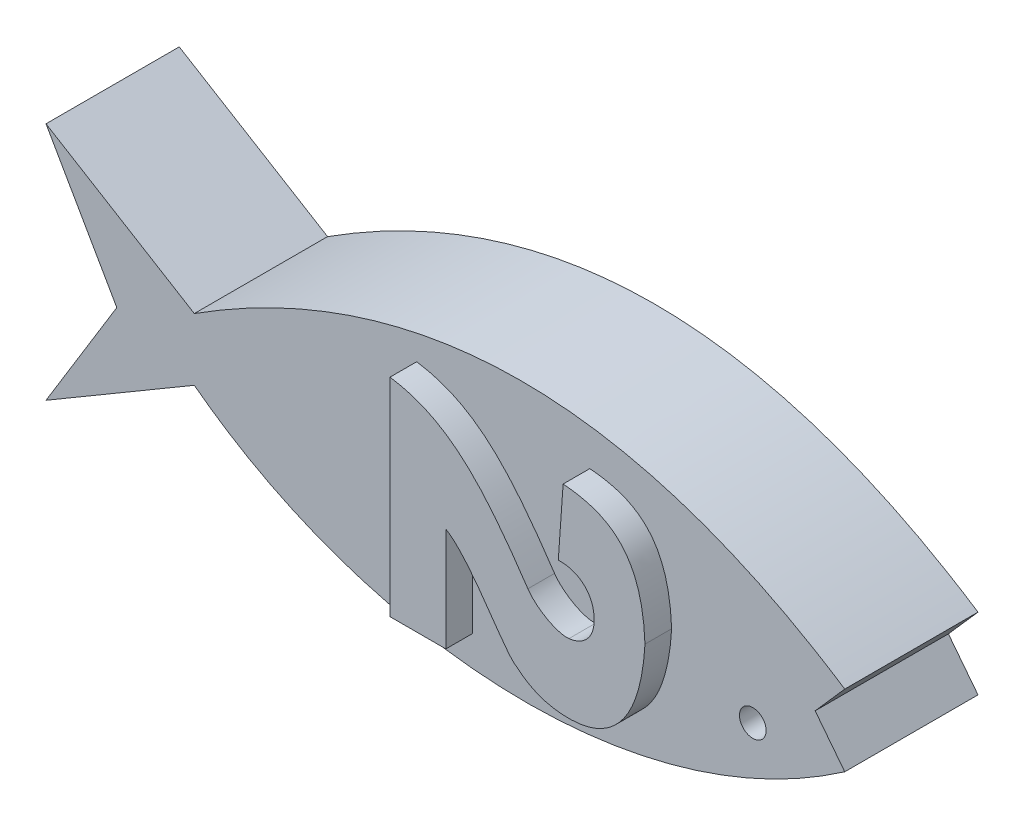
SolidWorks part; units mm, degrees
ref_plane "Front" through (0, 0, 0) normal (0, 0, 1) x (1, 0, 0)
ref_plane "Top" through (0, 0, 0) normal (0, 1, 0) x (1, 0, 0)
ref_plane "Right" through (0, 0, 0) normal (1, 0, 0) x (0, 0, -1)
sketch "Sketch2" plane through (0, 0, 0) normal (0, 0, -1) x (1, 0, 0)
  line L0 (29.973, 6.6427) -> (28.8624, 5.2157)
  line L1 (28.8624, 5.2157) -> (29.973, 3.9538)
  line L2 (5.5653, 6.2857) -> (0, 9.5561)
  line L3 (0, 9.5561) -> (2.6565, 5.2157)
  line L4 (2.6565, 5.2157) -> (0, 0.5701)
  line L5 (0, 0.5701) -> (5.5653, 3.9538)
  circle A0 centre (26.5226, 6.7807) radius 0.5001
  spline S0 degree 3 poles (5.5653, 6.2857) (12.0373, 11.2173) (22.1418, 12.0787) (29.973, 6.6427) knots 0 0 0 0 1 1 1 1
  spline S1 degree 2 poles (5.5653, 3.9538) (17.9191, -3.9397) (29.973, 3.9538) knots 0 0 0 1 1 1
extrude "Boss-Extrude1" add sketch "Sketch2" against normal blind 5
ref_plane "Fish Top Plane" through (0, 0, 5) normal (0, 0, 1) x (-1, 0, 0)
sketch "Sketch4" plane through (0, 0, 5) normal (0, 0, 1) x (-1, 0, 0)
  line L0 (-13.9083, 1.3496) -> (-13.9083, 9.134)
  line L1 (-13.9083, 9.134) -> (-16.0046, 9.134)
  line L2 (-16.0046, 9.134) -> (-16.0046, 5.2418)
  line L3 (-20.4045, 1.5754) -> (-20.2233, 4.1408)
  line L4 (6.7428, 13.444) -> (6.7428, -6.0128) construction
  line L5 (6.7428, -6.0128) -> (25.741, -6.0128) construction
  spline S0 degree 3 poles (-13.9083, 1.3496) (-16.1256, 1.6709) (-17.4379, 3.2047) (-19.0826, 5.6393) knots 0 0 0 0 1 1 1 1
  spline S1 degree 3 poles (-19.0826, 5.6393) (-19.4099, 6.1259) (-20.2102, 6.5446) (-20.6239, 6.4875) knots 0 0 0 0 1 1 1 1
  spline S2 degree 3 poles (-20.6239, 6.4875) (-21.0935, 6.4352) (-21.5578, 6.1026) (-21.5696, 5.4314) knots 0 0 0 0 1 1 1 1
  spline S3 degree 3 poles (-21.5696, 5.4314) (-21.5828, 4.4849) (-20.8434, 4.0961) (-20.2233, 4.1408) knots 0 0 0 0 1 1 1 1
  spline S4 degree 3 poles (-16.0046, 5.2418) (-16.9542, 5.7854) (-18.2215, 8.1724) (-18.647, 8.3688) knots 0 0 0 0 1 1 1 1
  spline S5 degree 3 poles (-18.647, 8.3688) (-19.1823, 8.8567) (-19.8662, 9.1022) (-20.6983, 9.0849) knots 0 0 0 0 1 1 1 1
  spline S6 degree 3 poles (-20.6983, 9.0849) (-22.3503, 9.0401) (-23.3308, 7.7628) (-23.4765, 5.2418) knots 0 0 0 0 1 1 1 1
  spline S7 degree 3 poles (-20.4045, 1.5754) (-22.3343, 1.7154) (-23.3817, 2.6691) (-23.4765, 5.2418) knots 0 0 0 0 1 1 1 1
extrude "Boss-Extrude2" add sketch "Sketch4" along normal blind 1
